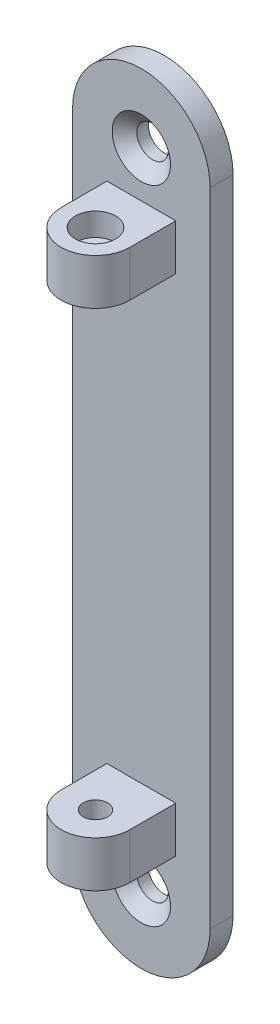
SolidWorks part; units mm, degrees
material "Plain Carbon Steel"
ref_plane "Front Plane" through (0, 0, 0) normal (0, 0, 1) x (1, 0, 0)
ref_plane "Top Plane" through (0, 0, 0) normal (0, 1, 0) x (1, 0, 0)
ref_plane "Right Plane" through (0, 0, 0) normal (1, 0, 0) x (0, 0, -1)
sketch "Sketch1" plane through (0, 0, 0) normal (0, 0, 1) x (1, 0, 0)
  line L0 (0, 0) -> (0, 88.9)
  line L1 (38.1, 88.9) -> (38.1, 0)
  line L2 (38.1, 0) -> (0, 0)
  arc A0 (0, 88.9) -> (38.1, 88.9) centre (19.05, 88.9) cw
  dimension "D2" = 19.05
  dimension "D1" = 88.9
extrude "Boss-Extrude1" add sketch "Sketch1" along normal blind 6.35
hole_wizard "CSK for 5/16 Flat Head Machine Screw (100)1" positions "Sketch4" profile "Sketch5" countersink size "5/16" standard "ANSI Inch" end condition through all
sketch "Sketch4" plane through (0, 0, 6.35) normal (0, 0, 1) x (1, 0, 0)
  arc A2 (38.1, 88.9) -> (0, 88.9) centre (19.05, 88.9) ccw construction
  point P0 (19.05, 88.9)
  point P10 (0, 0)
sketch "Sketch5" plane through (19.05, 88.9, 6.35) normal (1, 0, 0) x (0, -1, 0)
  line L0 (0, 0) -> (0, 6.35)
  line L1 (0, 6.35) -> (4.365, 6.35)
  line L2 (4.365, 6.35) -> (4.365, 3.1043)
  line L3 (4.365, 3.1043) -> (8.0645, 0)
  line L5 (8.0645, 0) -> (0, 0)
  line L6 (-4.365, 3.1043) -> (-8.0645, 0) construction
  line L11 (0, -6.35) -> (0, 107.95) construction
  dimension "Thru Hole Dia." = 8.73
  dimension "Thru Hole Depth" = 6.35
  dimension "Near C'Sink Dia." = 16.129
  dimension "Near C'Sink Angle" = 100
sketch "Sketch6" plane through (0, 0, 6.35) normal (0, 0, 1) x (1, 0, 0)
  line L4 (19.05, 0) -> (19.05, 69.85) construction
  line L5 (0, 0) -> (38.1, 0) construction
  line L7 (9.525, 63.5) -> (28.575, 63.5)
  line L8 (9.525, 63.5) -> (9.525, 76.2)
  line L9 (9.525, 76.2) -> (28.575, 76.2)
  line L10 (28.575, 63.5) -> (28.575, 76.2)
  line L11 (9.525, 63.5) -> (28.575, 76.2) construction
  line L12 (9.525, 76.2) -> (28.575, 63.5) construction
  dimension "D1" = 19.05
  dimension "D2" = 63.5
  dimension "D3" = 12.7
extrude "Boss-Extrude4" add sketch "Sketch6" along normal blind 12.7
sketch "Sketch12" plane through (0, 76.2, 0) normal (0, 1, 0) x (1, 0, 0)
  line L0 (9.525, -19.05) -> (28.575, -19.05)
  arc A0 (9.525, -19.05) -> (28.575, -19.05) centre (19.05, -19.05) ccw
extrude "Boss-Extrude7" add sketch "Sketch12" against normal up to surface (12.7 mm away) up to face at (19.05, 63.5, 12.7)
hole_wizard "CBORE for 1/4 Socket Head Cap Screw1" positions "Sketch13" profile "Sketch15" counterbore size "1/4" standard "ANSI Inch"
sketch "Sketch13" plane through (0, 76.2, 0) normal (0, 1, 0) x (1, 0, 0)
  arc A0 (9.525, -19.05) -> (28.575, -19.05) centre (19.05, -19.05) ccw construction
  point P0 (19.05, -19.05)
sketch "Sketch15" plane through (19.05, 76.2, 19.05) normal (1, 0, 0) x (0, 0, 1)
  line L0 (0, 0) -> (0, 14.7288)
  line L1 (0, 14.7288) -> (3.3782, 12.699)
  line L2 (3.3782, 12.699) -> (3.3782, 6.35)
  line L3 (3.3782, 6.35) -> (5.5562, 6.35)
  line L4 (5.5562, 6.35) -> (5.5562, 0)
  line L5 (5.5562, 0) -> (0, 0)
  line L10 (0, 14.7288) -> (-3.3782, 12.699) construction
  line L11 (0, -6.35) -> (0, 107.95) construction
  dimension "Hole Dia." = 6.7564
  dimension "Hole Depth" = 12.699
  dimension "C'Bore Dia." = 11.1125
  dimension "C'Bore Depth" = 6.35
  dimension "Drill Angle" = 118
mirror "Mirror1" about plane through (38.1, 0, 6.35) normal (0, 1, 0) of bodies 107
